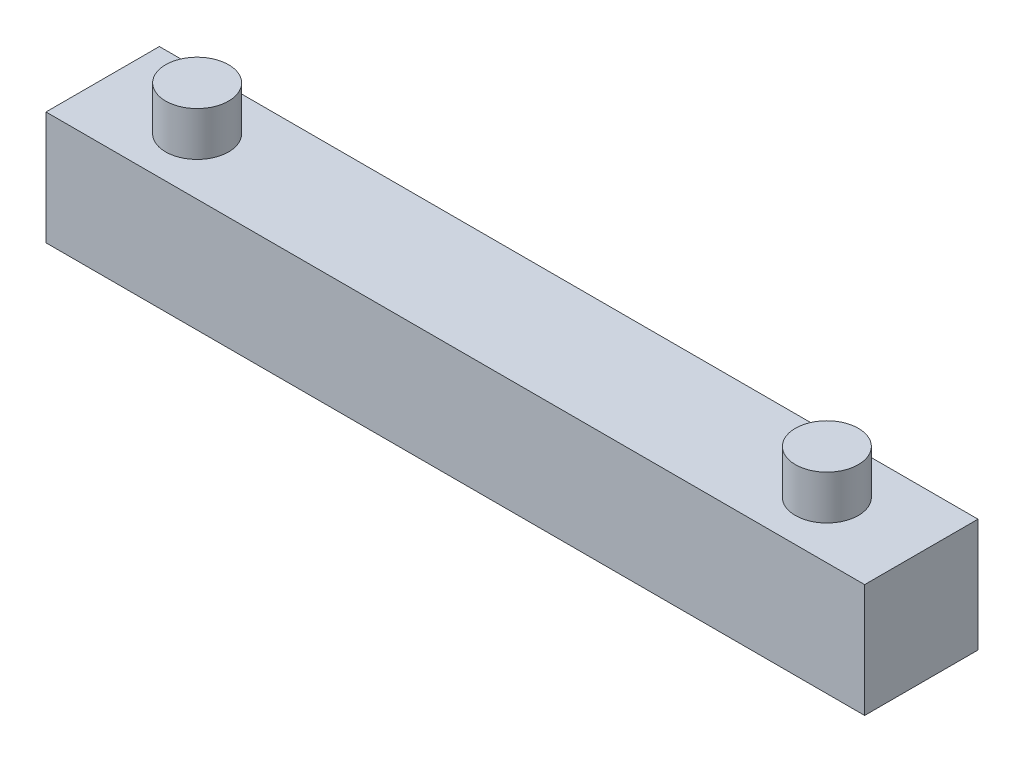
SolidWorks part; units mm, degrees
ref_plane "前基準面" through (0, 0, 0) normal (0, 0, 1) x (1, 0, 0)
ref_plane "上基準面" through (0, 0, 0) normal (0, 1, 0) x (1, 0, 0)
ref_plane "右基準面" through (0, 0, 0) normal (1, 0, 0) x (0, 0, -1)
sketch "草圖1" plane through (0, 0, 0) normal (0, 1, 0) x (1, 0, 0)
  line L1 (0, 0) -> (65, 0)
  line L2 (0, 0) -> (0, -9)
  line L3 (0, -9) -> (65, -9)
  line L4 (65, 0) -> (65, -9)
  dimension "D1" = 9
  dimension "D2" = 65
extrude "填料-伸長1" add sketch "草圖1" along normal blind 9
sketch "草圖2" plane through (0, 9, 0) normal (0, 1, 0) x (1, 0, 0)
  line L0 (0, 0) -> (7.5, 0)
  line L1 (65, 0) -> (0, 0) construction
  line L2 (7.5, 0) -> (7.5, -9.9584)
  line L3 (-0.8908, -4.5) -> (13.5742, -4.5)
  circle A0 centre (7.5, -4.5) radius 2.5
  dimension "D3" = 5
  dimension "D1" = 7.5
  dimension "D2" = 4.5
extrude "填料-伸長2" add sketch "草圖2" along normal blind 3.5 contours L2 A0 L3 | L3 A0 L2 | L2 A0 L3 | L3 A0 L2
sketch "草圖3" plane through (0, 9, 0) normal (0, 1, 0) x (1, 0, 0)
  line L0 (7.5, -4.5) -> (57.5, -4.5)
  circle A0 centre (57.5, -4.5) radius 2.5
  dimension "D2" = 5
  dimension "D1" = 50
extrude "填料-伸長3" add sketch "草圖3" along normal blind 3.5
